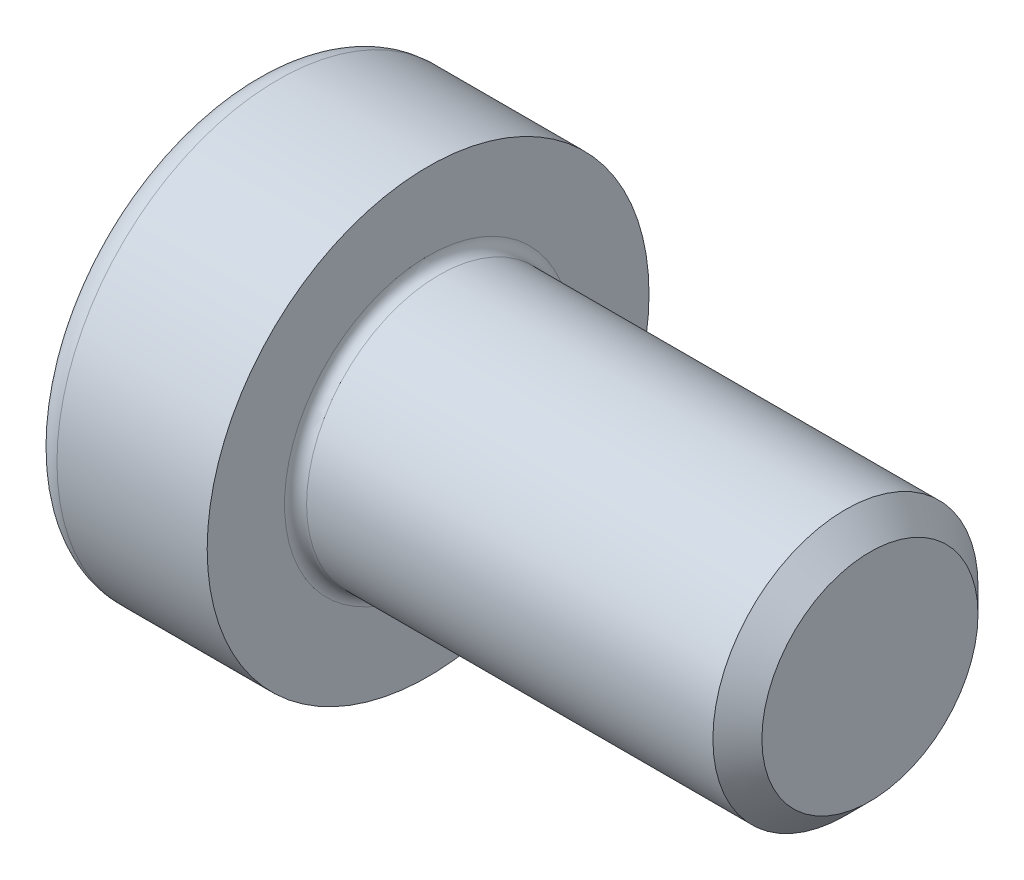
SolidWorks part; units mm, degrees
revolve "Base-Revolve" add sketch "BodySke"
sketch "BodySke" plane through (0, 0, 0) normal (0, 0, 1) x (1, 0, 0)
  line L0 (0, 0) -> (0, 5)
  line L1 (0, 5) -> (4, 5)
  line L2 (4, 5) -> (4, 3)
  line L3 (4, 3) -> (13.4455, 3)
  line L4 (14, 2.4455) -> (14, 0)
  line L5 (14, 0) -> (0, 0)
  line L6 (-31.75, 0) -> (127, 0) construction
  line L8 (14, 2.4455) -> (13.4455, 3)
  line L10 (14, -2.4455) -> (13.4455, -3) construction
  line L11 (5, 4.525) -> (5, -1.825) construction
  line L12 (4, 4.525) -> (4, -1.825) construction
  line L13 (-46, 4.525) -> (-46, -1.825) construction
  dimension "Head_ht" = 4
  dimension "Length" = 10
  dimension "Body_ch_ang" = 45
  dimension "Diameter" = 6
  dimension "Minor_dia" = 4.891
  dimension "Advance" = 1
  dimension "Thread_nom" = 10
  dimension "Thread_length" = 60
  dimension "Head_dia" = 10
cosmetic thread "ThreadCosmetic" [suppressed]
fillet "Fillet1" radius 0.25 1 edges at (4, 0, 3)
fillet "Fillet2" radius 0.6 1 edges at (0, 0, 5)
material "Stahl verzinkt"
ref_plane "Plane1" through (0, 0, 0) normal (0, 0, 1) x (1, 0, 0)
ref_plane "Plane2" through (0, 0, 0) normal (0, 1, 0) x (1, 0, 0)
ref_plane "Plane3" through (0, 0, 0) normal (1, 0, 0) x (0, 0, -1)
sketch "HexSke" plane through (0, 0, 0) normal (-1, 0, 0) x (0, 0.5, 0.866)
  line L0 (1.4434, 2.5) -> (-1.4434, 2.5)
  line L1 (-1.4434, 2.5) -> (-2.8868, 0)
  line L2 (1.4434, 2.5) -> (2.8868, 0)
  line L3 (1.4434, -2.5) -> (2.8868, 0)
  line L4 (1.4434, -2.5) -> (-1.4434, -2.5)
  line L5 (-1.4434, -2.5) -> (-2.8868, 0)
  dimension "D1" = 2.5
  dimension "D2" = 2.5
  dimension "Hex_size" = 5
extrude "Hex" cut sketch "HexSke" against normal blind 2.5
sketch "PilotSke" plane through (0, 0, 0) normal (0, 0, 1) x (1, 0, 0)
  line L0 (0, 2.5) -> (2.5, 2.5)
  line L1 (2.5, 2.5) -> (3.0774, 1.5)
  line L2 (-31.75, 0) -> (127, 0) construction
  line L3 (5.866, 0) -> (0, 0)
  line L4 (0, 0) -> (0, 2.5)
  line L5 (3.0774, 1.5) -> (5, 1.5)
  line L6 (0, 0) -> (47.625, 0) construction
  line L7 (5, 1.5) -> (5.866, 0)
  dimension "D1" = 2.5
  dimension "D2" = 60
  dimension "Depth" = 2.5
  dimension "Pilot_dia" = 3
  dimension "Pilot_Depth" = 5
revolve "Hex-PreBroach" cut sketch "PilotSke" angle 360 about L6
sketch "ThdSchSke" plane through (0, 0, 0) normal (0, 0, 1) x (1, 0, 0)
  line L0 (7, -2.4455) -> (6.6117, -3)
  line L1 (7, -2.4455) -> (7.3883, -3)
  line L2 (7.3883, -3) -> (7.3883, -3.75)
  line L3 (-3.175, 0) -> (5.1513, 0) construction
  line L4 (0, 4.4) -> (0, -4.4) construction
  line L5 (7.3883, -3.75) -> (6.6117, -3.75)
  line L6 (6.6117, -3.75) -> (6.6117, -3)
  dimension "Thread_minor" = 4.891
  dimension "Diameter" = 6
  dimension "Start" = 7
revolve "ThreadSchematic" [suppressed] cut sketch "ThdSchSke" angle 360 about L3
pattern_linear "ThdSchPat" [suppressed]
equation "\"D2@HexSke\" = \"Hex_size@HexSke\" / 2"
equation "\"D1@HexSke\" = \"Hex_size@HexSke\" / 2"
equation "\"D1@PilotSke\" = \"Hex_size@HexSke\" / 2"
equation "\"Thread_minor@ThreadCosmetic\"  =  \"Minor_dia@BodySke\""
equation "\"Depth@PilotSke\" =  \"Key_eng@Hex\""
equation "\"Thread_length@ThreadCosmetic\" = ((sgn( (\"Length@BodySke\" - \"Advance@BodySke\" * 3.0) - \"Thread_nom@BodySke\" )-1)*( (\"Length@BodySke\" - \"Advance@BodySke\" * 3.0) - \"Thread_nom@BodySke\" ))/-2+ \"Thread_nom@BodySke\""
equation "\"Thread_minor@ThdSchSke\" = \"Minor_dia@BodySke\""
equation "\"Diameter@ThdSchSke\" = \"Diameter@BodySke\""
equation "\"Overcut@ThdSchSke\" = \"Diameter@BodySke\" * 1.25"
equation "\"Start@ThdSchSke\" = \"Head_ht@BodySke\" + \"Length@BodySke\" - \"Thread_length@ThreadCosmetic\"  '---Non-countersunk---"
equation "\"Num_threads@ThdSchPat\" = int( \"Thread_length@ThreadCosmetic\" / \"Advance@BodySke\" + 0.999 )  + 1"
equation "\"Advance@ThdSchPat\" = \"Thread_length@ThreadCosmetic\" /  (\"Num_threads@ThdSchPat\" - 1) 'relax it"
equation "\"Num_threads@ThdSchPat\" = \"Num_threads@ThdSchPat\" - sgn( \"Num_threads@ThdSchPat\" - 1) '---chamfered tips only---"
